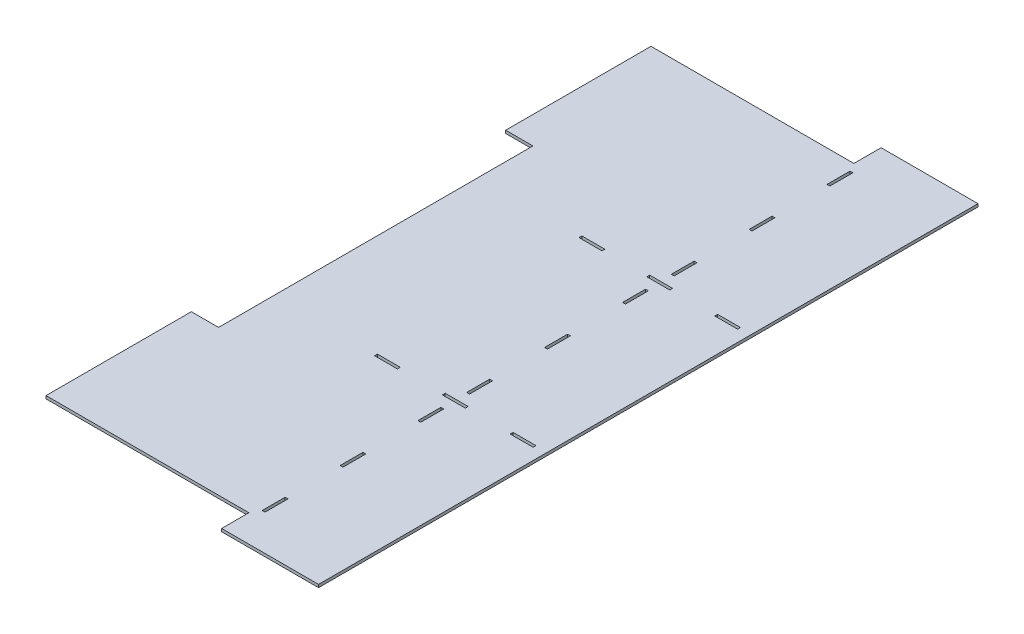
SolidWorks part; units mm, degrees
material "6061-T6 (SS)"
ref_plane "X-Y Datum" through (0, 0, 0) normal (0, 0, 1) x (1, 0, 0)
ref_plane "X-Z Datum" through (0, 0, 0) normal (0, 1, 0) x (1, 0, 0)
ref_plane "Y-Z Datum" through (0, 0, 0) normal (1, 0, 0) x (0, 0, -1)
sketch "Sketch2" plane through (0, 0, 0) normal (0, 1, 0) x (1, 0, 0)
  line L0 (204.155, 220.1367) -> (204.155, 223.3117)
  line L1 (0, 0) -> (95.7275, 0)
  line L2 (0, 0) -> (0, 216.9617)
  line L3 (0, 216.9617) -> (95.7275, 216.9617)
  line L4 (95.7275, 0) -> (95.7275, 216.9617)
  line L5 (95.7275, 216.9617) -> (98.9025, 216.9617)
  line L6 (95.7275, 216.9617) -> (95.7275, 0)
  line L7 (95.7275, 0) -> (98.9025, 0)
  line L8 (98.9025, 216.9617) -> (98.9025, 0)
  line L9 (98.9025, 216.9617) -> (102.0775, 216.9617)
  line L10 (98.9025, 216.9617) -> (98.9025, 0)
  line L11 (98.9025, 0) -> (102.0775, 0)
  line L12 (100.49, 216.9617) -> (100.49, 0)
  line L17 (0, 216.9617) -> (200.98, 216.9617)
  line L18 (0, 216.9617) -> (0, 220.1367)
  line L19 (0, 220.1367) -> (200.98, 220.1367)
  line L20 (100.49, 216.9617) -> (100.49, 220.1367)
  line L21 (0, 220.1367) -> (-3.175, 220.1367)
  line L22 (0, 220.1367) -> (0, 0)
  line L23 (0, 0) -> (-3.175, 0)
  line L24 (-3.175, 220.1367) -> (-3.175, 0)
  line L25 (-3.175, 0) -> (204.155, 0)
  line L26 (-3.175, 0) -> (-3.175, -3.175)
  line L27 (-3.175, -3.175) -> (204.155, -3.175)
  line L28 (100.49, 0) -> (100.49, -3.175)
  line L29 (-3.175, 220.1367) -> (204.155, 220.1367)
  line L30 (-3.175, 220.1367) -> (-3.175, 223.3117)
  line L31 (-3.175, 221.7242) -> (204.155, 221.7242)
  line L32 (100.49, 220.1367) -> (100.49, 223.3117)
  line L33 (200.98, 216.9617) -> (200.98, 220.1367)
  line L34 (102.0775, 216.9617) -> (102.0775, 0)
  line L35 (105.2525, 0) -> (102.0775, 0)
  line L36 (102.0775, 216.9617) -> (102.0775, 0)
  line L37 (105.2525, 216.9617) -> (102.0775, 216.9617)
  line L38 (105.2525, 216.9617) -> (105.2525, 0)
  line L39 (204.155, 0) -> (204.155, -3.175)
  line L40 (200.98, 216.9617) -> (105.2525, 216.9617)
  line L41 (105.2525, 0) -> (105.2525, 216.9617)
  line L42 (200.98, 0) -> (105.2525, 0)
  line L43 (200.98, 0) -> (200.98, 216.9617)
  line L44 (200.98, 0) -> (204.155, 0)
  line L45 (204.155, 220.1367) -> (204.155, 0)
  line L46 (200.98, 220.1367) -> (204.155, 220.1367)
  line L47 (200.98, 220.1367) -> (200.98, 0)
  line L48 (200.98, 223.3117) -> (200.98, 443.4484)
  line L49 (221.8451, -3.175) -> (221.8451, 221.7242) construction
  line L50 (200.98, 223.3117) -> (204.155, 223.3117)
  line L51 (204.155, 223.3117) -> (204.155, 443.4484)
  line L52 (200.98, 443.4484) -> (204.155, 443.4484)
  line L53 (200.98, 443.4484) -> (200.98, 226.4867)
  line L54 (200.98, 443.4484) -> (105.2525, 443.4484)
  line L55 (105.2525, 443.4484) -> (105.2525, 226.4867)
  line L56 (200.98, 226.4867) -> (105.2525, 226.4867)
  line L57 (204.155, 443.4484) -> (204.155, 446.6234)
  line L58 (105.2525, 226.4867) -> (105.2525, 443.4484)
  line L59 (105.2525, 226.4867) -> (102.0775, 226.4867)
  line L60 (102.0775, 226.4867) -> (102.0775, 443.4484)
  line L61 (105.2525, 443.4484) -> (102.0775, 443.4484)
  line L62 (102.0775, 226.4867) -> (102.0775, 443.4484)
  line L63 (200.98, 226.4867) -> (200.98, 223.3117)
  line L64 (-3.175, 223.3117) -> (204.155, 223.3117)
  line L65 (100.49, 443.4484) -> (100.49, 446.6234)
  line L66 (-3.175, 446.6234) -> (204.155, 446.6234)
  line L67 (-3.175, 443.4484) -> (-3.175, 446.6234)
  line L68 (-3.175, 443.4484) -> (204.155, 443.4484)
  line L69 (-3.175, 223.3117) -> (-3.175, 443.4484)
  line L70 (0, 443.4484) -> (-3.175, 443.4484)
  line L71 (0, 223.3117) -> (0, 443.4484)
  line L72 (0, 223.3117) -> (-3.175, 223.3117)
  line L73 (100.49, 226.4867) -> (100.49, 223.3117)
  line L74 (0, 223.3117) -> (200.98, 223.3117)
  line L75 (0, 226.4867) -> (0, 223.3117)
  line L76 (0, 226.4867) -> (200.98, 226.4867)
  line L77 (100.49, 226.4867) -> (100.49, 443.4484)
  line L78 (98.9025, 443.4484) -> (102.0775, 443.4484)
  line L79 (98.9025, 226.4867) -> (98.9025, 443.4484)
  line L80 (98.9025, 226.4867) -> (102.0775, 226.4867)
  line L81 (98.9025, 226.4867) -> (98.9025, 443.4484)
  line L82 (95.7275, 443.4484) -> (98.9025, 443.4484)
  line L83 (95.7275, 226.4867) -> (95.7275, 443.4484)
  line L84 (95.7275, 226.4867) -> (98.9025, 226.4867)
  line L85 (95.7275, 443.4484) -> (95.7275, 226.4867)
  line L86 (0, 226.4867) -> (95.7275, 226.4867)
  line L87 (0, 443.4484) -> (0, 226.4867)
  line L88 (0, 443.4484) -> (95.7275, 443.4484)
  line L90 (-3.175, 446.6234) -> (204.155, 446.6234)
  line L91 (-3.175, 446.6234) -> (-3.175, 449.7984)
  line L92 (-3.175, 448.2109) -> (204.155, 448.2109)
  line L93 (204.155, 446.6234) -> (204.155, 449.7984)
  line L94 (100.49, 669.9352) -> (100.49, 673.1102)
  line L95 (0, 669.9352) -> (200.98, 669.9352)
  line L96 (105.2525, 669.9352) -> (102.0775, 669.9352)
  line L97 (-3.175, 673.1102) -> (204.155, 673.1102)
  line L98 (200.98, 673.1102) -> (204.155, 673.1102)
  line L99 (200.98, 669.9352) -> (105.2525, 669.9352)
  line L100 (200.98, 452.9734) -> (204.155, 452.9734)
  line L101 (204.155, 673.1102) -> (204.155, 452.9734)
  line L102 (200.98, 673.1102) -> (200.98, 452.9734)
  line L103 (204.155, 452.9734) -> (204.155, 449.7984)
  line L104 (105.2525, 452.9734) -> (105.2525, 669.9352)
  line L105 (-3.175, 452.9734) -> (204.155, 452.9734)
  line L106 (105.2525, 452.9734) -> (102.0775, 452.9734)
  line L107 (102.0775, 669.9352) -> (102.0775, 452.9734)
  line L108 (100.49, 669.9352) -> (100.49, 452.9734)
  line L109 (95.7275, 669.9352) -> (95.7275, 452.9734)
  line L110 (98.9025, 669.9352) -> (98.9025, 452.9734)
  line L111 (100.49, 452.9734) -> (100.49, 449.7984)
  line L112 (0, 673.1102) -> (0, 452.9734)
  line L113 (-3.175, 673.1102) -> (-3.175, 452.9734)
  line L114 (-3.175, 452.9734) -> (-3.175, 449.7984)
  line L115 (-3.175, 449.7984) -> (204.155, 449.7984)
  line L116 (-3.175, 673.1102) -> (204.155, 673.1102)
  line L117 (-3.175, 673.1102) -> (-3.175, 676.2852)
  line L118 (-3.175, 676.2852) -> (204.155, 676.2852)
  line L119 (204.155, 673.1102) -> (204.155, 676.2852)
  point P41 (100.49, 221.7242)
  dimension "D1" = 95.7275
  dimension "D2" = 216.9617
  dimension "D3" = 3.175
  dimension "D4" = 1.5875
  dimension "D5" = 1.5875
  dimension "D6" = 3.175
  dimension "D7" = 3.175
  dimension "D8" = 3.175
  dimension "D9" = 1.5875
  dimension "D10" = 3.175
sketch "Sketch3" plane through (0, 0, 0) normal (0, 1, 0) x (1, 0, 0)
  line L0 (0, 448.2109) -> (12.7, 448.2109) construction
  line L3 (0, 0) -> (200.98, 0)
  line L4 (200.98, 669.9352) -> (200.98, 0)
  line L5 (-3.175, 448.2109) -> (204.155, 448.2109) construction
  line L6 (200.98, 448.2109) -> (188.28, 448.2109) construction
  line L7 (-3.175, 449.7984) -> (204.155, 449.7984) construction
  line L8 (12.7, 449.7984) -> (38.1, 449.7984)
  line L9 (12.7, 449.7984) -> (12.7, 446.6234)
  line L10 (12.7, 446.6234) -> (38.1, 446.6234)
  line L11 (38.1, 449.7984) -> (38.1, 446.6234)
  line L12 (-3.175, 446.6234) -> (204.155, 446.6234) construction
  line L13 (100.49, 673.1102) -> (100.49, 660.4102) construction
  line L14 (188.28, 449.7984) -> (162.88, 449.7984)
  line L15 (188.28, 449.7984) -> (188.28, 446.6234)
  line L16 (188.28, 446.6234) -> (162.88, 446.6234)
  line L17 (162.88, 449.7984) -> (162.88, 446.6234)
  line L18 (87.79, 446.6234) -> (113.19, 446.6234)
  line L19 (87.79, 446.6234) -> (87.79, 449.7984)
  line L20 (87.79, 449.7984) -> (113.19, 449.7984)
  line L21 (113.19, 446.6234) -> (113.19, 449.7984)
  line L22 (87.79, 446.6234) -> (113.19, 449.7984) construction
  line L23 (87.79, 449.7984) -> (113.19, 446.6234) construction
  line L24 (100.49, 669.9352) -> (100.49, 452.9734) construction
  line L25 (98.9025, 669.9352) -> (98.9025, 452.9734) construction
  line L26 (98.9025, 660.4102) -> (102.0775, 660.4102)
  line L27 (98.9025, 660.4102) -> (98.9025, 635.0102)
  line L28 (98.9025, 635.0102) -> (102.0775, 635.0102)
  line L29 (102.0775, 660.4102) -> (102.0775, 635.0102)
  line L30 (102.0775, 669.9352) -> (102.0775, 452.9734) construction
  line L31 (100.49, 449.7984) -> (100.49, 462.4984) construction
  line L32 (100.49, 635.0102) -> (100.49, 487.8984) construction
  line L33 (102.0775, 462.4984) -> (98.9025, 462.4984)
  line L34 (102.0775, 462.4984) -> (102.0775, 487.8984)
  line L35 (102.0775, 487.8984) -> (98.9025, 487.8984)
  line L36 (98.9025, 462.4984) -> (98.9025, 487.8984)
  line L37 (-14.5216, 448.2109) -> (228.7454, 448.2109) construction
  line L38 (98.9025, 548.7543) -> (102.0775, 548.7543)
  line L39 (98.9025, 548.7543) -> (98.9025, 574.1543)
  line L40 (98.9025, 574.1543) -> (102.0775, 574.1543)
  line L41 (102.0775, 548.7543) -> (102.0775, 574.1543)
  line L42 (98.9025, 548.7543) -> (102.0775, 574.1543) construction
  line L43 (98.9025, 574.1543) -> (102.0775, 548.7543) construction
  line L44 (102.0775, 408.5234) -> (98.9025, 408.5234)
  line L45 (98.9025, 433.9234) -> (98.9025, 408.5234)
  line L46 (102.0775, 433.9234) -> (98.9025, 433.9234)
  line L47 (102.0775, 433.9234) -> (102.0775, 408.5234)
  line L48 (98.9025, 322.2676) -> (102.0775, 322.2676)
  line L49 (102.0775, 347.6676) -> (102.0775, 322.2676)
  line L50 (98.9025, 347.6676) -> (102.0775, 347.6676)
  line L51 (98.9025, 347.6676) -> (98.9025, 322.2676)
  line L52 (98.9025, 261.4117) -> (102.0775, 261.4117)
  line L53 (102.0775, 236.0117) -> (102.0775, 261.4117)
  line L54 (98.9025, 236.0117) -> (102.0775, 236.0117)
  line L55 (98.9025, 236.0117) -> (98.9025, 261.4117)
  line L58 (-3.175, 223.3117) -> (204.155, 223.3117) construction
  line L59 (12.7, 223.3117) -> (38.1, 223.3117)
  line L60 (12.7, 223.3117) -> (12.7, 220.1367)
  line L61 (12.7, 220.1367) -> (38.1, 220.1367)
  line L62 (38.1, 223.3117) -> (38.1, 220.1367)
  line L63 (0, 220.1367) -> (200.98, 220.1367) construction
  line L64 (-6.8668, 221.7242) -> (213.4812, 221.7242) construction
  line L65 (87.79, 220.1367) -> (113.19, 220.1367)
  line L66 (87.79, 220.1367) -> (87.79, 223.3117)
  line L67 (87.79, 223.3117) -> (113.19, 223.3117)
  line L68 (113.19, 220.1367) -> (113.19, 223.3117)
  line L69 (87.79, 220.1367) -> (113.19, 223.3117) construction
  line L70 (87.79, 223.3117) -> (113.19, 220.1367) construction
  line L71 (188.28, 223.3117) -> (162.88, 223.3117)
  line L72 (188.28, 223.3117) -> (188.28, 220.1367)
  line L73 (188.28, 220.1367) -> (162.88, 220.1367)
  line L74 (162.88, 223.3117) -> (162.88, 220.1367)
  line L75 (102.0775, 9.525) -> (102.0775, 34.925)
  line L76 (102.0775, 9.525) -> (98.9025, 9.525)
  line L77 (98.9025, 9.525) -> (98.9025, 34.925)
  line L78 (102.0775, 34.925) -> (98.9025, 34.925)
  line L79 (98.9025, 95.7809) -> (98.9025, 121.1809)
  line L80 (98.9025, 95.7809) -> (102.0775, 95.7809)
  line L81 (102.0775, 95.7809) -> (102.0775, 121.1809)
  line L82 (98.9025, 121.1809) -> (102.0775, 121.1809)
  line L83 (98.9025, 207.4367) -> (98.9025, 182.0367)
  line L84 (98.9025, 207.4367) -> (102.0775, 207.4367)
  line L85 (102.0775, 207.4367) -> (102.0775, 182.0367)
  line L86 (98.9025, 182.0367) -> (102.0775, 182.0367)
  line L87 (-100.8126, 669.9352) -> (0, 669.9352)
  line L88 (0, 669.9352) -> (200.98, 669.9352)
  line L89 (-100.8126, 669.9352) -> (-100.8126, 0)
  line L90 (-100.8126, 0) -> (0, 0)
  point P24 (100.49, 448.2109)
  point P51 (100.49, 561.4543)
  point P81 (100.49, 221.7242)
  dimension "D1" = 12.7
  dimension "D2" = 25.4
extrude "Boss-Extrude1" add sketch "Sketch3" along normal blind 3.175
sketch "Sketch6" plane through (0, 3.175, 0) normal (0, 1, 0) x (1, 0, 0)
  line L0 (-100.8126, 334.9676) -> (342.6129, 334.9676) construction
  line L5 (200.98, 0) -> (93.6929, 0)
  line L6 (200.98, 0) -> (200.98, -30.1625)
  line L7 (200.98, -30.1625) -> (93.6929, -30.1625)
  line L8 (93.6929, 0) -> (93.6929, -30.1625)
  line L18 (200.98, 700.0977) -> (93.6929, 700.0977)
  line L19 (93.6929, 669.9352) -> (93.6929, 700.0977)
  line L20 (200.98, 669.9352) -> (93.6929, 669.9352)
  line L21 (200.98, 669.9352) -> (200.98, 700.0977)
  line L22 (-100.8126, 669.9352) -> (-130.9751, 669.9352)
  line L23 (-100.8126, 669.9352) -> (-100.8126, 509.0045)
  line L24 (-100.8126, 509.0045) -> (-130.9751, 509.0045)
  line L25 (-130.9751, 669.9352) -> (-130.9751, 509.0045)
  line L26 (-100.8126, 669.9352) -> (-100.8126, 0) construction
  line L27 (-130.9751, 0) -> (-130.9751, 160.9307)
  line L28 (-100.8126, 160.9307) -> (-130.9751, 160.9307)
  line L29 (-100.8126, 0) -> (-100.8126, 160.9307)
  line L30 (-100.8126, 0) -> (-130.9751, 0)
extrude "Boss-Extrude2" add sketch "Sketch6" against normal blind 3.175
